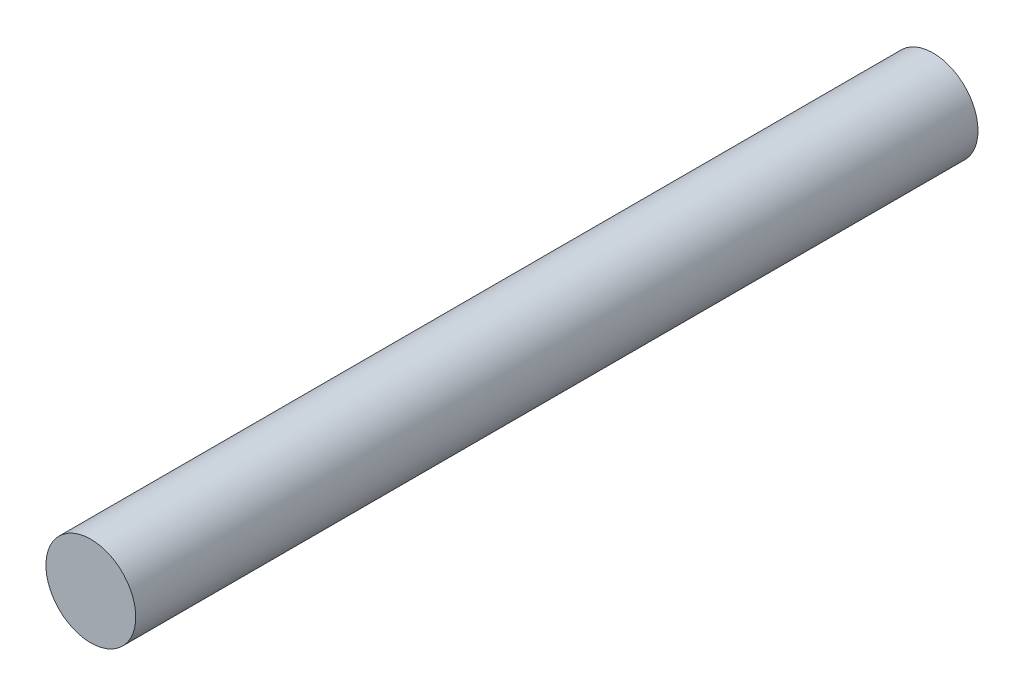
SolidWorks part; units mm, degrees
ref_plane "Front Plane" through (0, 0, 0) normal (0, 0, 1) x (1, 0, 0)
ref_plane "Top Plane" through (0, 0, 0) normal (0, 1, 0) x (1, 0, 0)
ref_plane "Right Plane" through (0, 0, 0) normal (1, 0, 0) x (0, 0, -1)
sketch "Sketch1" plane through (0, 0, 0) normal (0, 0, 1) x (1, 0, 0)
  circle A0 centre (36.3759, 14.1224) radius 0.8
extrude "Boss-Extrude1" add sketch "Sketch1" along normal blind 15
